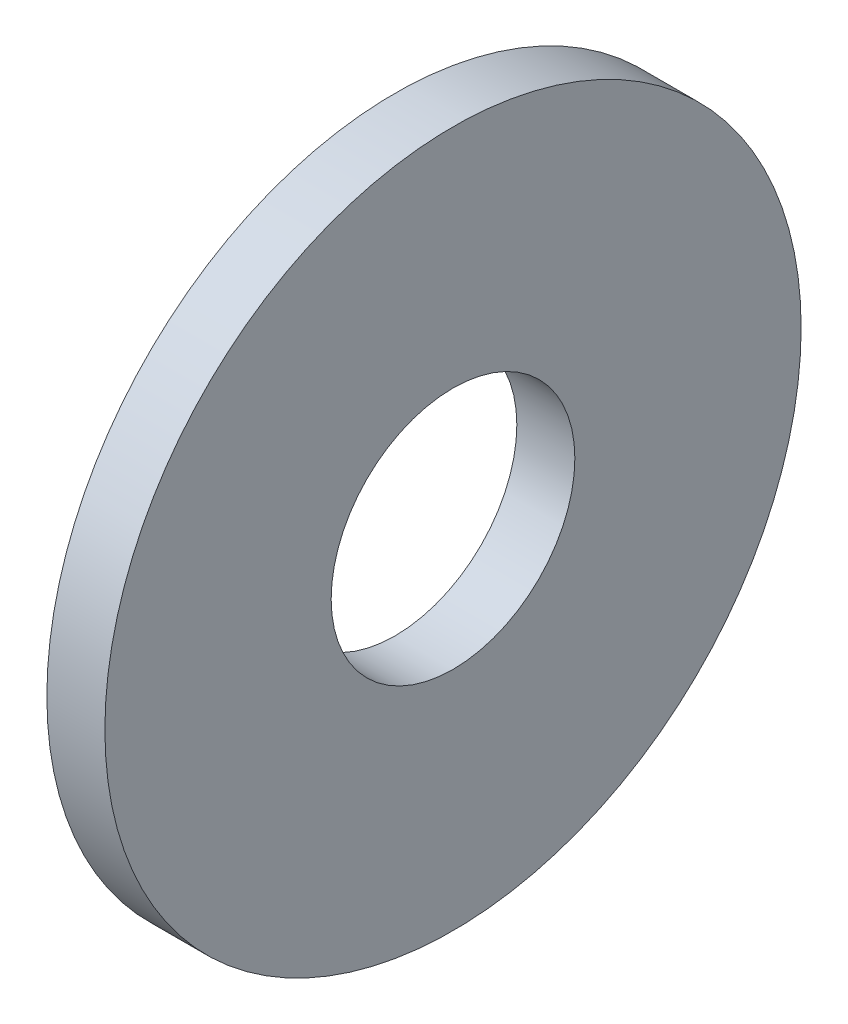
SolidWorks part; units mm, degrees
ref_plane "Plane1" through (0, 0, 0) normal (0, 0, 1) x (1, 0, 0)
ref_plane "Plane2" through (0, 0, 0) normal (0, 1, 0) x (1, 0, 0)
ref_plane "Plane3" through (0, 0, 0) normal (1, 0, 0) x (0, 0, -1)
sketch "Sketch1" plane through (0, 0, 0) normal (0, 0, 1) x (1, 0, 0)
  line L0 (-34.925, 0) -> (9.525, 0) construction
  line L1 (0, 4.2) -> (0, 12)
  line L2 (0, 12) -> (-2, 12)
  line L3 (-2, 12) -> (-2, 4.2)
  line L4 (-2, 4.2) -> (0, 4.2)
  dimension "Thickness" = 2
  dimension "Inside_dia" = 8.4
  dimension "Outside_dia" = 24
revolve "Base-Revolve" add sketch "Sketch1" angle 360 about L0
